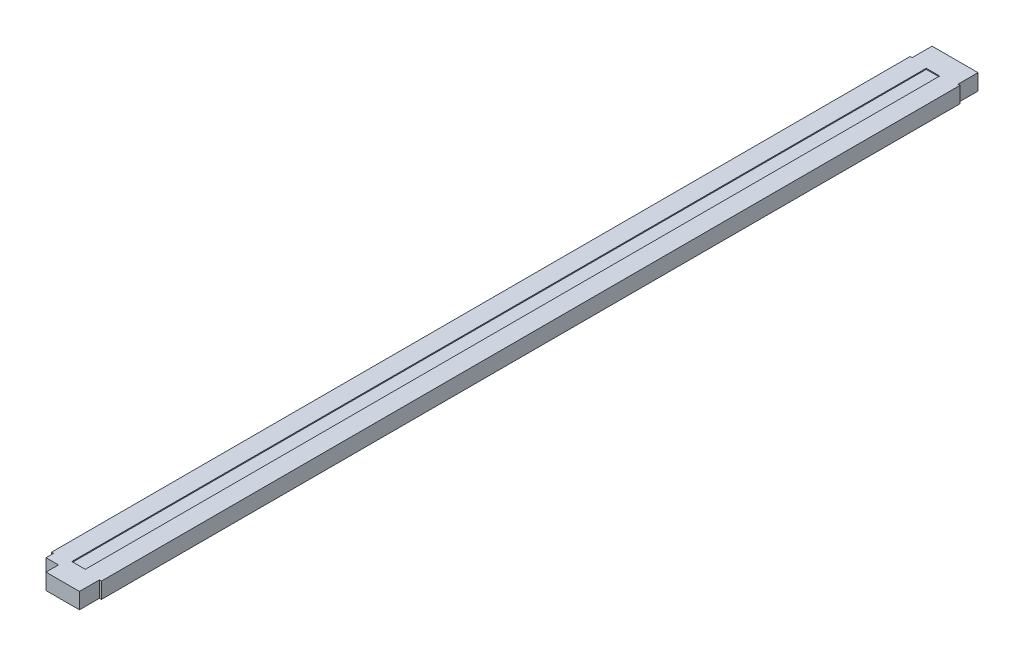
SolidWorks part; units mm, degrees
ref_plane "Front Plane" through (0, 0, 0) normal (0, 0, 1) x (1, 0, 0)
ref_plane "Top Plane" through (0, 0, 0) normal (0, 1, 0) x (1, 0, 0)
ref_plane "Right Plane" through (0, 0, 0) normal (1, 0, 0) x (0, 0, -1)
sketch "Sketch1" plane through (0, 0, 0) normal (0, 0, 1) x (1, 0, 0)
  line L1 (-6.35, -2.032) -> (6.35, -2.032)
  line L2 (-6.35, -2.032) -> (-6.35, 2.032)
  line L3 (-6.35, 2.032) -> (6.35, 2.032)
  line L4 (6.35, -2.032) -> (6.35, 2.032)
  line L5 (-6.35, -2.032) -> (6.35, 2.032) construction
  line L6 (-6.35, 2.032) -> (6.35, -2.032) construction
  point P0 (0, 0)
  dimension "D1" = 4.064
  dimension "D2" = 12.7
extrude "Boss-Extrude1" add sketch "Sketch1" along normal blind 228.6
sketch "Sketch2" plane through (0, 2.032, 0) normal (0, 1, 0) x (1, 0, 0)
  line L0 (1.7145, -114.3) -> (6.35, -114.3) construction
  line L1 (-1.7145, -5.6134) -> (1.7145, -5.6134)
  line L2 (-1.7145, -5.6134) -> (-1.7145, -222.9866)
  line L3 (-1.7145, -222.9866) -> (1.7145, -222.9866)
  line L4 (1.7145, -5.6134) -> (1.7145, -222.9866)
  line L5 (6.35, -228.6) -> (6.35, 0) construction
  line L6 (-1.7145, -114.3) -> (-6.35, -114.3) construction
  line L7 (-6.35, -228.6) -> (-6.35, 0) construction
  dimension "D1" = 3.429
  dimension "D2" = 217.3732
extrude "Cut-Extrude1" cut sketch "Sketch2" against normal blind 0.254
sketch "Sketch3" plane through (0, 2.032, 0) normal (0, 1, 0) x (1, 0, 0)
  line L1 (-6.35, -228.6) -> (-5.842, -228.6)
  line L2 (-6.35, -228.6) -> (-6.35, -223.52)
  line L3 (-6.35, -223.52) -> (-5.842, -223.52)
  line L4 (-5.842, -228.6) -> (-5.842, -223.52)
  dimension "D1" = 0.508
  dimension "D2" = 5.08
extrude "Cut-Extrude2" cut sketch "Sketch3" against normal through all
ref_plane "Plane1" through (0, 0, 114.3) normal (0, 0, -1) x (-1, 0, 0)
mirror "Mirror1" about plane through (0, 0, 114.3) normal (0, 0, -1) of "Cut-Extrude2"
mirror "Mirror2" about plane through (0, 0, 0) normal (1, 0, 0) of "Mirror1", "Cut-Extrude2"
sketch "Sketch4" plane through (0, 2.032, 0) normal (0, 1, 0) x (1, 0, 0)
  line L2 (-5.842, -228.6) -> (-2.667, -228.6)
  line L3 (-5.842, -228.6) -> (-5.842, -225.425)
  line L4 (-5.842, -225.425) -> (-2.667, -225.425)
  line L5 (-2.667, -228.6) -> (-2.667, -225.425)
  dimension "D1" = 3.175
  dimension "D2" = 3.175
extrude "Cut-Extrude3" cut sketch "Sketch4" against normal through all
